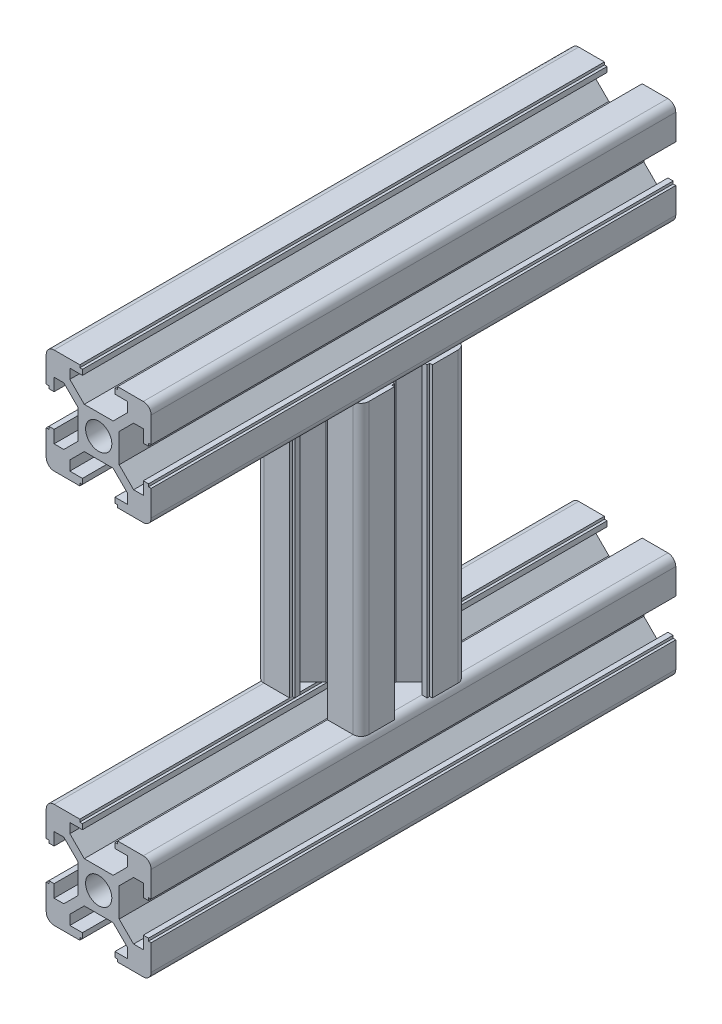
SolidWorks part; units mm, degrees
ref_plane "前视基准面" through (0, 0, 0) normal (0, 0, 1) x (1, 0, 0)
ref_plane "上视基准面" through (0, 0, 0) normal (0, 1, 0) x (1, 0, 0)
ref_plane "右视基准面" through (0, 0, 0) normal (1, 0, 0) x (0, 0, -1)
other "Configuration Table"
sketch "草图3" plane through (0, 0, 0) normal (0, 0, 1) x (1, 0, 0)
  line L0 (-3.6, 10) -> (-3.6, 9.5)
  line L1 (-3.6, 9.5) -> (-3.1, 9.5)
  line L2 (-3.1, 9.5) -> (-3.1, 8.5)
  line L3 (-3.1, 8.5) -> (-5.5, 8.5)
  line L4 (-8.5, -10) -> (-3.6, -10)
  line L5 (-10, -8.5) -> (-10, -3.6)
  line L6 (8.5, 10) -> (3.6, 10)
  line L7 (10, 8.5) -> (10, 3.6)
  line L8 (0, 14.8756) -> (0, 0) construction
  line L9 (0, 0) -> (14.1675, 0) construction
  line L10 (-5.5, 8.5) -> (-5.5, 6.65)
  line L11 (-5.5, 6.65) -> (-2.75, 3.9)
  line L12 (-2.75, 3.9) -> (2.75, 3.9)
  line L13 (5.5, 6.65) -> (2.75, 3.9)
  line L14 (5.5, 8.5) -> (5.5, 6.65)
  line L15 (3.1, 8.5) -> (5.5, 8.5)
  line L16 (3.1, 9.5) -> (3.1, 8.5)
  line L17 (3.6, 9.5) -> (3.1, 9.5)
  line L18 (3.6, 10) -> (3.6, 9.5)
  line L19 (-3.6, 10) -> (-8.5, 10)
  line L20 (10, 3.6) -> (9.5, 3.6)
  line L21 (9.5, 3.6) -> (9.5, 3.1)
  line L22 (9.5, 3.1) -> (8.5, 3.1)
  line L23 (8.5, 3.1) -> (8.5, 5.5)
  line L24 (8.5, 5.5) -> (6.65, 5.5)
  line L25 (6.65, 5.5) -> (3.9, 2.75)
  line L26 (3.9, 2.75) -> (3.9, -2.75)
  line L27 (6.65, -5.5) -> (3.9, -2.75)
  line L28 (8.5, -5.5) -> (6.65, -5.5)
  line L29 (8.5, -3.1) -> (8.5, -5.5)
  line L30 (9.5, -3.1) -> (8.5, -3.1)
  line L31 (9.5, -3.6) -> (9.5, -3.1)
  line L32 (10, -3.6) -> (9.5, -3.6)
  line L33 (3.6, -10) -> (3.6, -9.5)
  line L34 (3.6, -9.5) -> (3.1, -9.5)
  line L35 (3.1, -9.5) -> (3.1, -8.5)
  line L36 (3.1, -8.5) -> (5.5, -8.5)
  line L37 (5.5, -8.5) -> (5.5, -6.65)
  line L38 (5.5, -6.65) -> (2.75, -3.9)
  line L39 (2.75, -3.9) -> (-2.75, -3.9)
  line L40 (-5.5, -6.65) -> (-2.75, -3.9)
  line L41 (-5.5, -8.5) -> (-5.5, -6.65)
  line L42 (-3.1, -8.5) -> (-5.5, -8.5)
  line L43 (-3.1, -9.5) -> (-3.1, -8.5)
  line L44 (-3.6, -9.5) -> (-3.1, -9.5)
  line L45 (-3.6, -10) -> (-3.6, -9.5)
  line L46 (-10, -3.6) -> (-9.5, -3.6)
  line L47 (-9.5, -3.6) -> (-9.5, -3.1)
  line L48 (-9.5, -3.1) -> (-8.5, -3.1)
  line L49 (-8.5, -3.1) -> (-8.5, -5.5)
  line L50 (-8.5, -5.5) -> (-6.65, -5.5)
  line L51 (-6.65, -5.5) -> (-3.9, -2.75)
  line L52 (-3.9, -2.75) -> (-3.9, 2.75)
  line L53 (-6.65, 5.5) -> (-3.9, 2.75)
  line L54 (-8.5, 5.5) -> (-6.65, 5.5)
  line L55 (-8.5, 3.1) -> (-8.5, 5.5)
  line L56 (-9.5, 3.1) -> (-8.5, 3.1)
  line L57 (-9.5, 3.6) -> (-9.5, 3.1)
  line L58 (-10, 3.6) -> (-9.5, 3.6)
  line L59 (3.6, -10) -> (8.5, -10)
  line L60 (-10, 3.6) -> (-10, 8.5)
  line L61 (10, -3.6) -> (10, -8.5)
  circle A0 centre (0, 0) radius 2.5
  arc A1 (-10, 8.5) -> (-8.5, 10) centre (-8.5, 8.5) cw
  arc A2 (10, 8.5) -> (8.5, 10) centre (8.5, 8.5) ccw
  arc A3 (-8.5, -10) -> (-10, -8.5) centre (-8.5, -8.5) cw
  arc A4 (8.5, -10) -> (10, -8.5) centre (8.5, -8.5) ccw
  point P0 (-10, 0)
  point P1 (10, 0)
  point P2 (0, 10)
  point P3 (0, -10)
  point P4 (0, 0)
  point P5 (-10, -10)
  point P6 (10, -10)
  point P7 (10, 10)
  point P8 (-10, 10)
  point P36 (-10, 10)
  point P39 (10, 10)
  dimension "D1" = 11
  dimension "D2" = 20
  dimension "D3" = 6.2
  dimension "D4" = 7.2
  dimension "D5" = 6.1
  dimension "D6" = 5
  dimension "D7" = 1.5
  dimension "D8" = 45
  dimension "D9" = 0.5
  dimension "D10" = 1
  dimension "D11" = 5.5
extrude "凸台-拉伸3" add sketch "草图3" along normal blind 100
sketch "草图6" plane through (0, 0, 0) normal (0, 1, 0) x (1, 0, 0)
  line L0 (-3.6, -40) -> (-3.6, -40.5)
  line L1 (-3.6, -40.5) -> (-3.1, -40.5)
  line L2 (-3.1, -40.5) -> (-3.1, -41.5)
  line L3 (-3.1, -41.5) -> (-5.5, -41.5)
  line L4 (-8.5, -60) -> (-3.6, -60)
  line L5 (-10, -58.5) -> (-10, -53.6)
  line L6 (8.5, -40) -> (3.6, -40)
  line L7 (10, -41.5) -> (10, -46.4)
  line L8 (0, 14.8756) -> (0, -50) construction
  line L9 (0, -50) -> (14.1675, -50) construction
  line L10 (-5.5, -41.5) -> (-5.5, -43.35)
  line L11 (-5.5, -43.35) -> (-2.75, -46.1)
  line L12 (-2.75, -46.1) -> (2.75, -46.1)
  line L13 (5.5, -43.35) -> (2.75, -46.1)
  line L14 (5.5, -41.5) -> (5.5, -43.35)
  line L15 (3.1, -41.5) -> (5.5, -41.5)
  line L16 (3.1, -40.5) -> (3.1, -41.5)
  line L17 (3.6, -40.5) -> (3.1, -40.5)
  line L18 (3.6, -40) -> (3.6, -40.5)
  line L19 (-3.6, -40) -> (-8.5, -40)
  line L20 (10, -46.4) -> (9.5, -46.4)
  line L21 (9.5, -46.4) -> (9.5, -46.9)
  line L22 (9.5, -46.9) -> (8.5, -46.9)
  line L23 (8.5, -46.9) -> (8.5, -44.5)
  line L24 (8.5, -44.5) -> (6.65, -44.5)
  line L25 (6.65, -44.5) -> (3.9, -47.25)
  line L26 (3.9, -47.25) -> (3.9, -52.75)
  line L27 (6.65, -55.5) -> (3.9, -52.75)
  line L28 (8.5, -55.5) -> (6.65, -55.5)
  line L29 (8.5, -53.1) -> (8.5, -55.5)
  line L30 (9.5, -53.1) -> (8.5, -53.1)
  line L31 (9.5, -53.6) -> (9.5, -53.1)
  line L32 (10, -53.6) -> (9.5, -53.6)
  line L33 (3.6, -60) -> (3.6, -59.5)
  line L34 (3.6, -59.5) -> (3.1, -59.5)
  line L35 (3.1, -59.5) -> (3.1, -58.5)
  line L36 (3.1, -58.5) -> (5.5, -58.5)
  line L37 (5.5, -58.5) -> (5.5, -56.65)
  line L38 (5.5, -56.65) -> (2.75, -53.9)
  line L39 (2.75, -53.9) -> (-2.75, -53.9)
  line L40 (-5.5, -56.65) -> (-2.75, -53.9)
  line L41 (-5.5, -58.5) -> (-5.5, -56.65)
  line L42 (-3.1, -58.5) -> (-5.5, -58.5)
  line L43 (-3.1, -59.5) -> (-3.1, -58.5)
  line L44 (-3.6, -59.5) -> (-3.1, -59.5)
  line L45 (-3.6, -60) -> (-3.6, -59.5)
  line L46 (-10, -53.6) -> (-9.5, -53.6)
  line L47 (-9.5, -53.6) -> (-9.5, -53.1)
  line L48 (-9.5, -53.1) -> (-8.5, -53.1)
  line L49 (-8.5, -53.1) -> (-8.5, -55.5)
  line L50 (-8.5, -55.5) -> (-6.65, -55.5)
  line L51 (-6.65, -55.5) -> (-3.9, -52.75)
  line L52 (-3.9, -52.75) -> (-3.9, -47.25)
  line L53 (-6.65, -44.5) -> (-3.9, -47.25)
  line L54 (-8.5, -44.5) -> (-6.65, -44.5)
  line L55 (-8.5, -46.9) -> (-8.5, -44.5)
  line L56 (-9.5, -46.9) -> (-8.5, -46.9)
  line L57 (-9.5, -46.4) -> (-9.5, -46.9)
  line L58 (-10, -46.4) -> (-9.5, -46.4)
  line L59 (3.6, -60) -> (8.5, -60)
  line L60 (-10, -46.4) -> (-10, -41.5)
  line L61 (10, -53.6) -> (10, -58.5)
  line L63 (8.5, -100) -> (3.6, -100) construction
  circle A0 centre (0, -50) radius 2.5
  arc A1 (-10, -41.5) -> (-8.5, -40) centre (-8.5, -41.5) cw
  arc A2 (10, -41.5) -> (8.5, -40) centre (8.5, -41.5) ccw
  arc A3 (-8.5, -60) -> (-10, -58.5) centre (-8.5, -58.5) cw
  arc A4 (8.5, -60) -> (10, -58.5) centre (8.5, -58.5) ccw
  point P0 (-10, 0)
  point P1 (10, -50)
  point P2 (0, 10)
  point P3 (0, -10)
  point P4 (0, 0)
  point P5 (-10, -60)
  point P6 (10, -60)
  point P7 (10, -40)
  point P8 (-10, -40)
  point P36 (-10, -40)
  point P39 (10, -40)
  dimension "D1" = 11
  dimension "D2" = 20
  dimension "D3" = 6.2
  dimension "D4" = 7.2
  dimension "D5" = 6.1
  dimension "D6" = 5
  dimension "D7" = 1.5
  dimension "D8" = 45
  dimension "D9" = 0.5
  dimension "D10" = 1
  dimension "D11" = 5.5
  dimension "D13" = 50
  dimension "D12" = 4
extrude "凸台-拉伸9" add sketch "草图6" along normal blind 55 from surface at 10 separate body starting at face at (-6.05, 10, 50)
sketch "草图7" plane through (0, 0, 46.1) normal (0, 0, -1) x (-1, 0, 0)
  line L0 (-3.6, 85) -> (-3.6, 84.5)
  line L1 (-3.6, 84.5) -> (-3.1, 84.5)
  line L2 (-3.1, 84.5) -> (-3.1, 83.5)
  line L3 (-3.1, 83.5) -> (-5.5, 83.5)
  line L4 (-8.5, 65) -> (-3.6, 65)
  line L5 (-10, 66.5) -> (-10, 71.4)
  line L6 (8.5, 85) -> (3.6, 85)
  line L7 (10, 83.5) -> (10, 78.6)
  line L8 (0, 94.8756) -> (0, 75) construction
  line L9 (0, 75) -> (11.4966, 75) construction
  line L10 (-5.5, 83.5) -> (-5.5, 81.65)
  line L11 (-5.5, 81.65) -> (-2.75, 78.9)
  line L12 (-2.75, 78.9) -> (2.75, 78.9)
  line L13 (5.5, 81.65) -> (2.75, 78.9)
  line L14 (5.5, 83.5) -> (5.5, 81.65)
  line L15 (3.1, 83.5) -> (5.5, 83.5)
  line L16 (3.1, 84.5) -> (3.1, 83.5)
  line L17 (3.6, 84.5) -> (3.1, 84.5)
  line L18 (3.6, 85) -> (3.6, 84.5)
  line L19 (-3.6, 85) -> (-8.5, 85)
  line L20 (10, 78.6) -> (9.5, 78.6)
  line L21 (9.5, 78.6) -> (9.5, 78.1)
  line L22 (9.5, 78.1) -> (8.5, 78.1)
  line L23 (8.5, 78.1) -> (8.5, 80.5)
  line L24 (8.5, 80.5) -> (6.65, 80.5)
  line L25 (6.65, 80.5) -> (3.9, 77.75)
  line L26 (3.9, 77.75) -> (3.9, 72.25)
  line L27 (6.65, 69.5) -> (3.9, 72.25)
  line L28 (8.5, 69.5) -> (6.65, 69.5)
  line L29 (8.5, 71.9) -> (8.5, 69.5)
  line L30 (9.5, 71.9) -> (8.5, 71.9)
  line L31 (9.5, 71.4) -> (9.5, 71.9)
  line L32 (10, 71.4) -> (9.5, 71.4)
  line L33 (3.6, 65) -> (3.6, 65.5)
  line L34 (3.6, 65.5) -> (3.1, 65.5)
  line L35 (3.1, 65.5) -> (3.1, 66.5)
  line L36 (3.1, 66.5) -> (5.5, 66.5)
  line L37 (5.5, 66.5) -> (5.5, 68.35)
  line L38 (5.5, 68.35) -> (2.75, 71.1)
  line L39 (2.75, 71.1) -> (-2.75, 71.1)
  line L40 (-5.5, 68.35) -> (-2.75, 71.1)
  line L41 (-5.5, 66.5) -> (-5.5, 68.35)
  line L42 (-3.1, 66.5) -> (-5.5, 66.5)
  line L43 (-3.1, 65.5) -> (-3.1, 66.5)
  line L44 (-3.6, 65.5) -> (-3.1, 65.5)
  line L45 (-3.6, 65) -> (-3.6, 65.5)
  line L46 (-10, 71.4) -> (-9.5, 71.4)
  line L47 (-9.5, 71.4) -> (-9.5, 71.9)
  line L48 (-9.5, 71.9) -> (-8.5, 71.9)
  line L49 (-8.5, 71.9) -> (-8.5, 69.5)
  line L50 (-8.5, 69.5) -> (-6.65, 69.5)
  line L51 (-6.65, 69.5) -> (-3.9, 72.25)
  line L52 (-3.9, 72.25) -> (-3.9, 77.75)
  line L53 (-6.65, 80.5) -> (-3.9, 77.75)
  line L54 (-8.5, 80.5) -> (-6.65, 80.5)
  line L55 (-8.5, 78.1) -> (-8.5, 80.5)
  line L56 (-9.5, 78.1) -> (-8.5, 78.1)
  line L57 (-9.5, 78.6) -> (-9.5, 78.1)
  line L58 (-10, 78.6) -> (-9.5, 78.6)
  line L59 (3.6, 65) -> (8.5, 65)
  line L60 (-10, 78.6) -> (-10, 83.5)
  line L61 (10, 71.4) -> (10, 66.5)
  line L62 (3.6, 10) -> (8.5, 10) construction
  line L63 (10, -3.6) -> (10, -8.5) construction
  circle A0 centre (0, 75) radius 2.5
  arc A1 (-10, 83.5) -> (-8.5, 85) centre (-8.5, 83.5) cw
  arc A2 (10, 83.5) -> (8.5, 85) centre (8.5, 83.5) ccw
  arc A3 (-8.5, 65) -> (-10, 66.5) centre (-8.5, 66.5) cw
  arc A4 (8.5, 65) -> (10, 66.5) centre (8.5, 66.5) ccw
  point P0 (-12.6708, 34.3669)
  point P1 (7.3292, 75)
  point P2 (-2.6708, 44.3669)
  point P3 (-2.6708, 24.3669)
  point P4 (-2.6708, 34.3669)
  point P5 (-10, 65)
  point P6 (10, 65)
  point P7 (10, 85)
  point P8 (-10, 85)
  point P36 (-10, 85)
  point P39 (10, 85)
  point P44 (6.05, 10)
  dimension "D1" = 11
  dimension "D2" = 20
  dimension "D3" = 6.2
  dimension "D4" = 7.2
  dimension "D5" = 6.1
  dimension "D6" = 5
  dimension "D7" = 1.5
  dimension "D8" = 45
  dimension "D9" = 0.5
  dimension "D10" = 1
  dimension "D11" = 5.5
  dimension "D12" = 55
  dimension "D13" = 10
extrude "凸台-拉伸10" add sketch "草图7" along normal blind 100 from surface at -53.9 separate body starting at face at (0, 0, 100)
